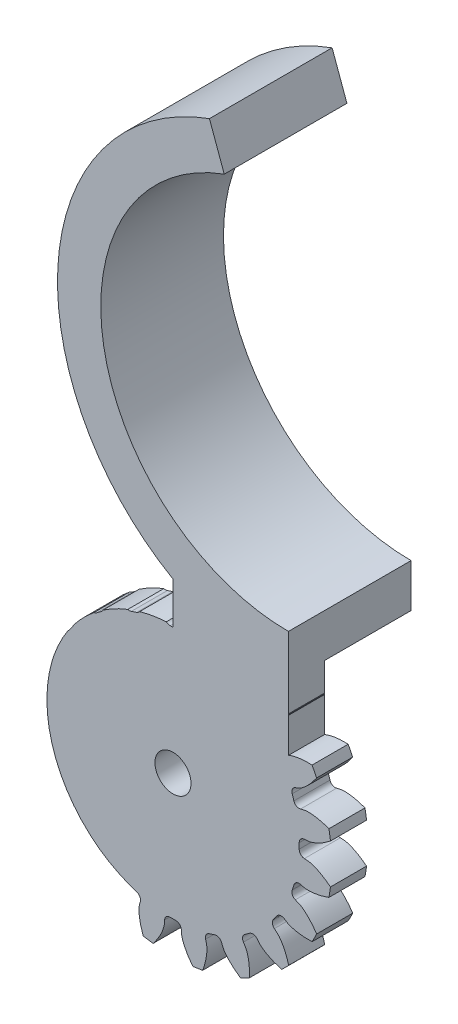
SolidWorks part; units mm, degrees
ref_plane "前视基准面" through (0, 0, 0) normal (0, 0, 1) x (1, 0, 0)
ref_plane "上视基准面" through (0, 0, 0) normal (0, 1, 0) x (1, 0, 0)
ref_plane "右视基准面" through (0, 0, 0) normal (1, 0, 0) x (0, 0, -1)
ref_axis "Axis1" through (0, 0, -88.99) along (0, 0, 1)
sketch "草图1" plane through (0, 0, 0) normal (0, 0, 1) x (1, 0, 0)
  circle A0 centre (0, 0) radius 22
extrude "LaShenA" add sketch "草图1" along normal blind 5
sketch "SketchA" plane through (0, 0, 5) normal (0, 0, 1) x (1, 0, 0)
  line L0 (0, 0) -> (0, 22) construction
  arc A0 (0.3853, 17.4958) -> (-0.3853, 17.4958) centre (0, 0) ccw
  arc A1 (3.5863, 22.7662) -> (-3.5863, 22.7662) centre (0, 0) ccw
  arc A2 (-0.3853, 17.4958) -> (-1.1606, 18.2089) centre (-0.4021, 18.2556) cw
  arc A3 (1.1606, 18.2089) -> (0.3853, 17.4958) centre (0.4021, 18.2556) cw
  circle A4 centre (0, 0) radius 18.7939 construction
  circle A5 centre (0, 0) radius 22 construction
  circle A6 centre (0, 0) radius 17.5 construction
  circle A7 centre (0, 0) radius 20 construction
  spline S0 degree 3 poles (1.1606, 18.2089) (1.1719, 18.3923) (1.1762, 18.6326) (1.2161, 18.8968) (1.2407, 19.0085) (1.2625, 19.0969) (1.2905, 19.1982) (1.3253, 19.3121) (1.3676, 19.4382) (1.4182, 19.5763) (1.4777, 19.7261) (1.5468, 19.887) (1.6261, 20.0586) (1.7163, 20.2406) (1.8179, 20.4325) (1.9317, 20.6337) (2.0581, 20.8437) (2.1978, 21.062) (2.3512, 21.288) (2.5189, 21.5211) (2.7014, 21.7607) (2.8992, 22.0061) (3.1899, 22.3474) (3.4232, 22.5992) (3.5863, 22.7662) knots 0.125068 0.125068 0.125068 0.125068 0.215847 0.244833 0.257593 0.272674 0.290074 0.309794 0.331834 0.356194 0.382875 0.411875 0.443195 0.476835 0.512796 0.551076 0.591676 0.634597 0.679837 0.727398 0.777278 0.829478 0.883999 1 1 1 1
  spline S1 degree 3 poles (-1.1606, 18.2089) (-1.1719, 18.3923) (-1.1762, 18.6326) (-1.2161, 18.8968) (-1.2407, 19.0085) (-1.2625, 19.0969) (-1.2905, 19.1982) (-1.3253, 19.3121) (-1.3676, 19.4382) (-1.4182, 19.5763) (-1.4777, 19.7261) (-1.5468, 19.887) (-1.6261, 20.0586) (-1.7163, 20.2406) (-1.8179, 20.4325) (-1.9317, 20.6337) (-2.0581, 20.8437) (-2.1978, 21.062) (-2.3512, 21.288) (-2.5189, 21.5211) (-2.7014, 21.7607) (-2.8992, 22.0061) (-3.1899, 22.3474) (-3.4232, 22.5992) (-3.5863, 22.7662) knots 0.125068 0.125068 0.125068 0.125068 0.215847 0.244833 0.257593 0.272674 0.290074 0.309794 0.331834 0.356194 0.382875 0.411875 0.443195 0.476835 0.512796 0.551076 0.591676 0.634597 0.679837 0.727398 0.777278 0.829478 0.883999 1 1 1 1
  dimension "D1" = 0.76
  dimension "Db" = 37.5877
  dimension "Da" = 44
  dimension "Df" = 35
  dimension "Dn" = 40
extrude "Cut-ExtrudeA" cut sketch "SketchA" against normal blind 50
pattern_circular "www.KYTool.cn" count 20 over 360 about axis through (0, 0, -88.99) along (0, 0, 1) of "Cut-ExtrudeA"
sketch "草图2" plane through (0, 0, 0) normal (0, 0, -1) x (-1, 0, 0)
  line L0 (-16, 0) -> (-16, 25)
  line L1 (-7.1075, 75.432) -> (-5.0554, 81.0702)
  line L2 (-3, 28.4833) -> (0, 23.2872) construction
  line L3 (0, 23.2872) -> (0, 16)
  line L4 (-16, 77) -> (-16, 83) construction
  line L5 (-16, 51) -> (-16, 77) construction
  line L6 (-16, 51) -> (-3, 28.4833) construction
  line L7 (-16, 51) -> (-7.1075, 75.432) construction
  line L8 (-16, 25) -> (-16, 51) construction
  arc A0 (0, 16) -> (-16, 0) centre (0, 0) ccw
  arc A1 (-16, 25) -> (-7.1075, 75.432) centre (-16, 51) ccw
  arc A2 (0, 23.2872) -> (-5.0554, 81.0702) centre (-16, 51) ccw
  arc A3 (-16, 77) -> (-16, 25) centre (-16, 51) ccw construction
  arc A4 (-7.1075, 75.432) -> (-16, 77) centre (-16, 51) ccw construction
  arc A5 (-16, 83) -> (-16, 19) centre (-16, 51) ccw construction
  arc A6 (-5.0554, 81.0702) -> (-16, 83) centre (-16, 51) ccw construction
  arc A7 (-16, 19) -> (0, 23.2872) centre (-16, 51) ccw construction
  arc A8 (-16, 0) -> (0, 16) centre (0, 0) ccw construction
  point P5 (-16, 51)
  dimension "D1" = 32
  dimension "D4" = 52
  dimension "D2" = 83
  dimension "D3" = 51
  dimension "D5" = 20
  dimension "D6" = 30
extrude "凸台-拉伸1" add sketch "草图2" against normal blind 5
sketch "草图3" plane through (0, 0, 0) normal (0, 0, -1) x (-1, 0, 0)
  line L0 (-5.0554, 81.0702) -> (-7.1075, 75.432) construction
  line L1 (-5.0554, 81.0702) -> (-7.1075, 75.432)
  line L4 (-16, 25) -> (-16, 15.0997) construction
  line L5 (-16, 25) -> (-16, 19)
  arc A0 (-16, 25) -> (-7.1075, 75.432) centre (-16, 51) ccw construction
  arc A1 (0, 23.2872) -> (-5.0554, 81.0702) centre (-16, 51) ccw construction
  arc A2 (-16, 25) -> (-7.1075, 75.432) centre (-16, 51) ccw
  arc A3 (-16, 19) -> (-5.0554, 81.0702) centre (-16, 51) ccw
  arc A4 (-16, 25) -> (-3, 28.4833) centre (-16, 51) ccw construction
  arc A5 (-3, 28.4833) -> (-16, 25) centre (-16, 51) ccw construction
  arc A6 (0, 23.2872) -> (-16, 19) centre (-16, 51) ccw construction
extrude "凸台-拉伸2" add sketch "草图3" along normal blind 12
sketch "草图4" plane through (0, 0, 0) normal (0, 0, -1) x (-1, 0, 0)
  line L0 (0.9166, 17.6962) -> (0.9166, 23.5051)
  line L1 (0.9166, 23.5051) -> (17.2926, 22.1008)
  line L2 (17.2926, 22.1008) -> (29.5689, 0.0885)
  line L3 (29.5689, 0.0885) -> (13.2945, -24.5236)
  line L4 (13.2945, -24.5236) -> (5.773, -24.5236)
  line L5 (5.773, -24.5236) -> (5.773, -16.5204)
  circle A0 centre (0, 0) radius 2.5
  arc A1 (0.9166, 17.6962) -> (5.773, -16.5204) centre (-0.1737, 0.0885) cw
  arc A2 (0.3853, 17.4958) -> (1.1606, 18.2089) centre (0.4021, 18.2556) ccw construction
  dimension "D1" = 5
extrude "切除-拉伸1" cut sketch "草图4" against normal through all
